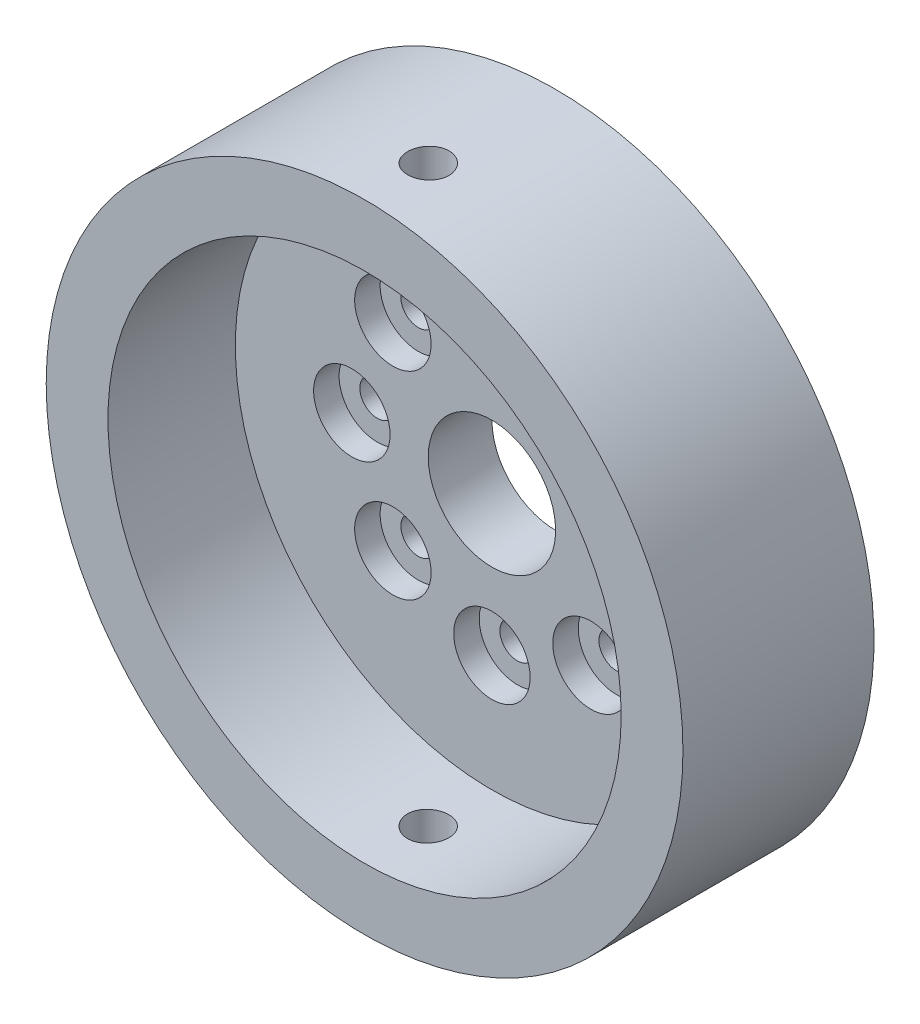
SolidWorks part; units mm, degrees
ref_plane "Front Plane" through (0, 0, 0) normal (0, 0, 1) x (1, 0, 0)
ref_plane "Top Plane" through (0, 0, 0) normal (0, 1, 0) x (1, 0, 0)
ref_plane "Right Plane" through (0, 0, 0) normal (1, 0, 0) x (0, 0, -1)
sketch "Sketch1" plane through (0, 0, 0) normal (0, 0, 1) x (1, 0, 0)
  circle A0 centre (0, 0) radius 20.15
  circle A1 centre (0, 0) radius 25
  dimension "D1" = 40.3
  dimension "D2" = 50
extrude "Boss-Extrude1" add sketch "Sketch1" along normal blind 10
sketch "Sketch2" plane through (0, 0, 0) normal (0, 0, -1) x (-1, 0, 0)
  circle A0 centre (0, 0) radius 11
  circle A1 centre (-11, 0) radius 1.375
  circle A2 centre (-7.7782, 7.7782) radius 1.375
  circle A3 centre (0, 11) radius 1.375
  circle A4 centre (7.7782, 7.7782) radius 1.375
  circle A5 centre (11, 0) radius 1.375
  circle A6 centre (7.7782, -7.7782) radius 1.375
  circle A7 centre (0, -11) radius 1.375
  circle A8 centre (-7.7782, -7.7782) radius 1.375
  circle A9 centre (0, 0) radius 5
  circle A10 centre (0, 0) radius 25
  point P26 (0, 0)
  circle M7 centre (0, 0) radius 25
  circle M8 centre (0, 0) radius 20.15
  dimension "D5" = 22
  dimension "D6" = 2.75
  dimension "D8" = 10
  dimension "D7" = 8
extrude "Boss-Extrude2" add sketch "Sketch2" along normal blind 5 contours A8 A0 A1 A2 A3 A4 A5 A6 A7 M8 | A8 A0 A7 A6 A5 A4 A3 A2 A1 A9 | M7 M8
sketch "Sketch3" plane through (0, 0, 0) normal (0, 0, 1) x (1, 0, 0)
  circle A0 centre (0, 11) radius 3
  circle A1 centre (7.7782, 7.7782) radius 3
  circle A2 centre (11, 0) radius 3
  circle A3 centre (7.7782, -7.7782) radius 3
  circle A4 centre (0, -11) radius 3
  circle A5 centre (-7.7782, -7.7782) radius 3
  circle A6 centre (-11, 0) radius 3
  circle A7 centre (-7.7782, 7.7782) radius 3
  point P19 (0, 0)
  dimension "D1" = 6
  dimension "D2" = 8
extrude "Cut-Extrude1" cut sketch "Sketch3" against normal blind 2
sketch "Sketch4" plane through (0, 0, 0) normal (0, 1, 0) x (1, 0, 0)
  line L0 (-20.15, 0) -> (20.15, 0) construction
  circle A0 centre (0, -5) radius 1.625
  dimension "D1" = 3.25
  dimension "D2" = 5
extrude "Cut-Extrude2" cut sketch "Sketch4" against normal blind 33 and the other way blind 38
